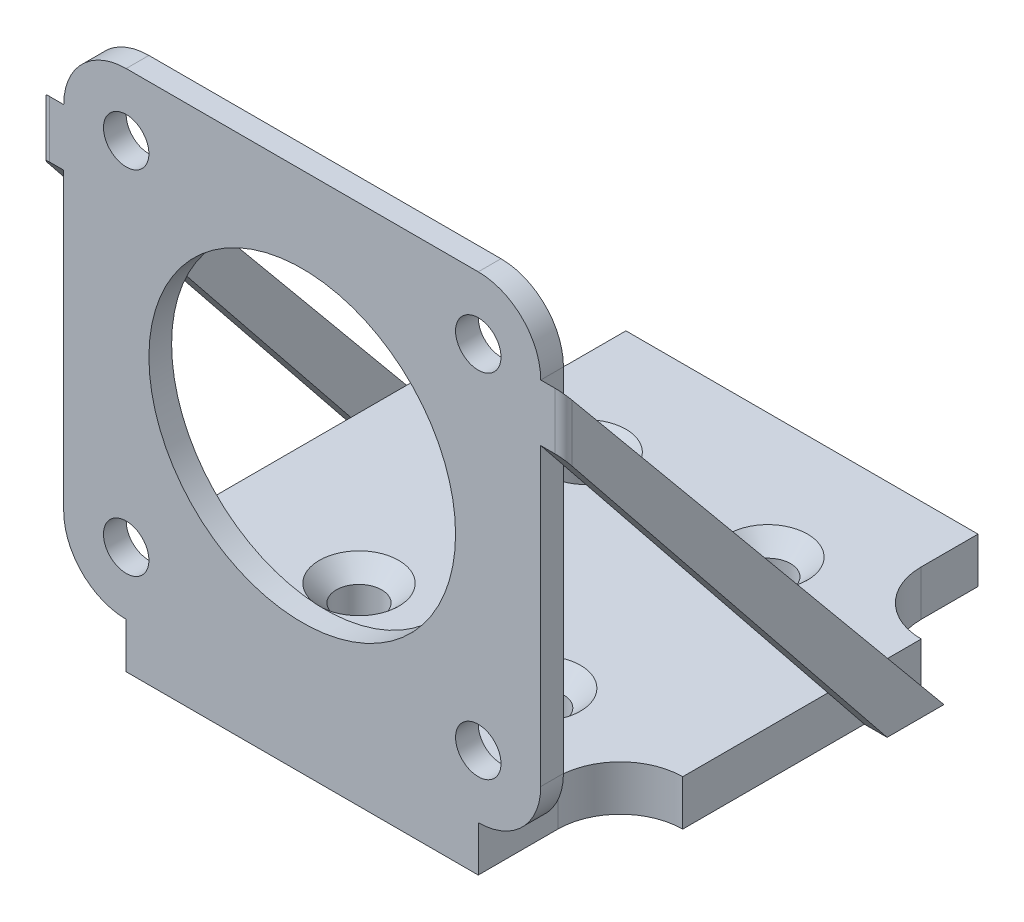
SolidWorks part; units mm, degrees
ref_plane "Front Plane" through (0, 0, 0) normal (0, 0, 1) x (1, 0, 0)
ref_plane "Top Plane" through (0, 0, 0) normal (0, 1, 0) x (1, 0, 0)
ref_plane "Right Plane" through (0, 0, 0) normal (1, 0, 0) x (0, 0, -1)
sketch "Sketch1" plane through (0, 0, 0) normal (0, 0, 1) x (1, 0, 0)
  line L0 (-21, 0) -> (21, 0) construction
  line L1 (-15.5, -21) -> (15.5, -21)
  line L2 (-21, -15.5) -> (-21, 15.5)
  line L3 (-15.5, 21) -> (15.5, 21)
  line L4 (21, -15.5) -> (21, 15.5)
  line L5 (0, 21) -> (0, -21) construction
  circle A0 centre (-15.5, 15.5) radius 2
  circle A1 centre (-15.5, -15.5) radius 2
  circle A2 centre (15.5, -15.5) radius 2
  circle A3 centre (15.5, 15.5) radius 2
  arc A4 (-15.5, 21) -> (-21, 15.5) centre (-15.5, 15.5) ccw
  arc A5 (21, -15.5) -> (15.5, -21) centre (15.5, -15.5) cw
  arc A6 (-15.5, -21) -> (-21, -15.5) centre (-15.5, -15.5) cw
  arc A7 (15.5, 21) -> (21, 15.5) centre (15.5, 15.5) cw
  circle A8 centre (0, 0) radius 13.5
  point P0 (0, 0)
  point P20 (-21, 21)
  dimension "D2" = 4
  dimension "D4" = 5.5
  dimension "D1" = 27
  dimension "D5" = 15.5
  dimension "D6" = 15.5
extrude "Boss-Extrude1" add sketch "Sketch1" along normal blind 2
ref_plane "Plane1" through (0, -21, 0) normal (0, 1, 0) x (1, 0, 0)
sketch "Sketch4" plane through (0, -21, 0) normal (0, 1, 0) x (1, 0, 0)
  line L0 (-15.5, 0) -> (-15.5, 5)
  line L1 (-21, 10.5) -> (-21, 31.5)
  line L2 (-15.5, 37) -> (-15.5, 42)
  line L3 (-15.5, 42) -> (15.5, 42)
  line L4 (0, 42) -> (0, 0) construction
  line L5 (15.5, 37) -> (15.5, 42)
  line L6 (21, 10.5) -> (21, 31.5)
  line L7 (15.5, 0) -> (15.5, 5)
  line L8 (-8, 0) -> (-8, 42) construction
  line L9 (15.5, 0) -> (-15.5, 0) construction
  line L10 (0, 21) -> (-21, 21) construction
  line L13 (-15.5, 0) -> (-15.5, -2)
  line L15 (-15.5, -2) -> (15.5, -2)
  line L16 (15.5, -2) -> (-15.5, -2) construction
  line L17 (15.5, -2) -> (15.5, 0)
  arc A0 (-15.5, 5) -> (-21, 10.5) centre (-21, 5) ccw
  arc A1 (-21, 31.5) -> (-15.5, 37) centre (-21, 37) ccw
  arc A2 (21, 31.5) -> (15.5, 37) centre (21, 37) cw
  arc A3 (15.5, 5) -> (21, 10.5) centre (21, 5) cw
  circle A4 centre (-8, 31) radius 2
  circle A5 centre (-8, 11) radius 2
  circle A6 centre (8, 31) radius 2
  circle A7 centre (8, 11) radius 2
  dimension "D3" = 8
  dimension "D5" = 10
  dimension "D6" = 4
  dimension "D1" = 42
  dimension "D2" = 5
  dimension "D4" = 21
extrude "Boss-Extrude2" add sketch "Sketch4" against normal blind 4 separate body
chamfer "Chamfer1" distance 1.5 angle 45 4 edges at (-8, -21, -13) (-8, -21, -29) (8, -21, -9) (8, -21, -33)
sketch "Sketch5" plane through (-21, 0, 0) normal (-1, 0, 0) x (0, 0, 1)
  line L0 (-26.5, -25) -> (2, 10.5)
  line L1 (-31.5, -25) -> (-10.5, -25) construction
  line L2 (2, 15.5) -> (2, -15.5) construction
  line L3 (2, 10.5) -> (2, 15.5)
  line L4 (2, 15.5) -> (-31.5, -25)
  line L5 (-31.5, -25) -> (-26.5, -25)
  line L6 (2, 15.5) -> (0, 15.5) construction
  dimension "D2" = 5
  dimension "D3" = 5
extrude "Boss-Extrude3" add sketch "Sketch5" along normal blind 2
mirror "Mirror5" about plane through (0, 0, 0) normal (1, 0, 0) of "Boss-Extrude3"
fillet "Fillet2" radius 0.75 1 edges at (23, 13, 2)
sketch "Sketch6" plane through (-23, 0, 0) normal (-1, 0, 0) x (0, 0, 1)
fillet "Fillet4" radius 0.75 1 edges at (-23, 13, 2)
